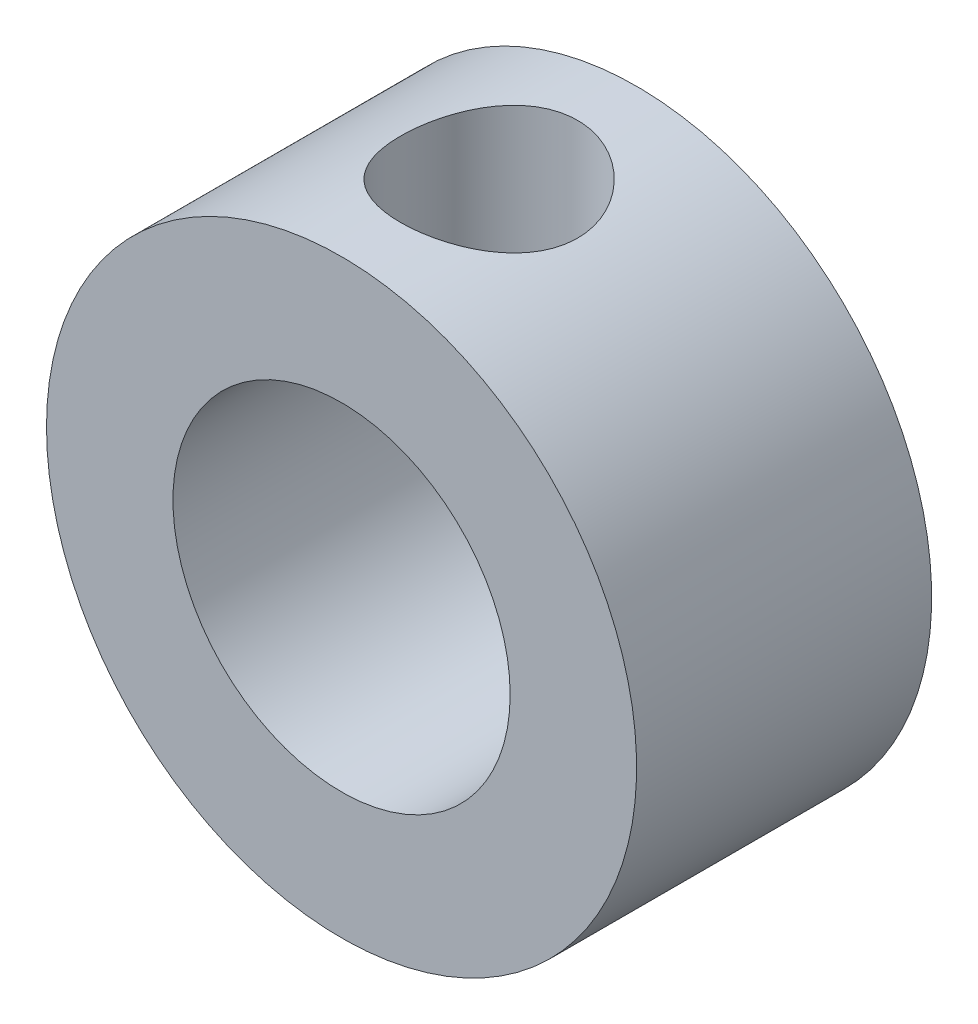
SolidWorks part; units mm, degrees
material "Stainless Steel (ferritic)"
ref_plane "Front Plane" through (0, 0, 0) normal (0, 0, 1) x (1, 0, 0)
ref_plane "Top Plane" through (0, 0, 0) normal (0, 1, 0) x (1, 0, 0)
ref_plane "Right Plane" through (0, 0, 0) normal (1, 0, 0) x (0, 0, -1)
ref_plane "Plane1" through (0, 0, 0) normal (0, -1, 0) x (1, 0, 0)
sketch "Sketch1" plane through (0, 0, 0) normal (0, -1, 0) x (1, 0, 0)
  line L0 (7, 7) -> (0, 7)
  line L1 (0, 7) -> (0, 0)
  line L2 (0, 0) -> (7, 0)
  line L3 (7, 0) -> (7, 7)
  line L4 (0, 7) -> (0, 0) construction
revolve "Revolve1" add sketch "Sketch1" angle 360 about L4
hole_wizard "Ø8.0 (8) Diameter Hole1" positions "Sketch3" profile "Sketch2" hole size "Ø8.0" standard "ANSI Metric"
sketch "Sketch3" plane through (0, 0, 7) normal (0, 0, 1) x (1, 0, 0)
  point P0 (0, 0)
sketch "Sketch2" plane through (0, 0, 7) normal (1, 0, 0) x (0, -1, 0)
  line L0 (0, 0) -> (0, 7)
  line L1 (0, 7) -> (4, 7)
  line L2 (4, 7) -> (4, 0)
  line L5 (4, 0) -> (0, 0)
  line L11 (0, -6.35) -> (0, 107.95) construction
  dimension "Thru Hole Dia." = 8
  dimension "Thru Hole Depth" = 7
hole_wizard "Ø4.2 (4.2) Diameter Hole1" positions "3DSketch1" profile "Sketch4" hole size "Ø4.2" standard "ANSI Metric"
sketch3d "3DSketch1"
  point P0 (0, 7, 3.5)
sketch "Sketch4" plane through (0, 7, 3.5) normal (1, 0, 0) x (0, 0, 1)
  line L0 (0, 0) -> (0, 3)
  line L1 (0, 3) -> (2.1, 3)
  line L2 (2.1, 3) -> (2.1, 0)
  line L5 (2.1, 0) -> (0, 0)
  line L11 (0, -6.35) -> (0, 107.95) construction
  dimension "Thru Hole Dia." = 4.2
  dimension "Thru Hole Depth" = 3
